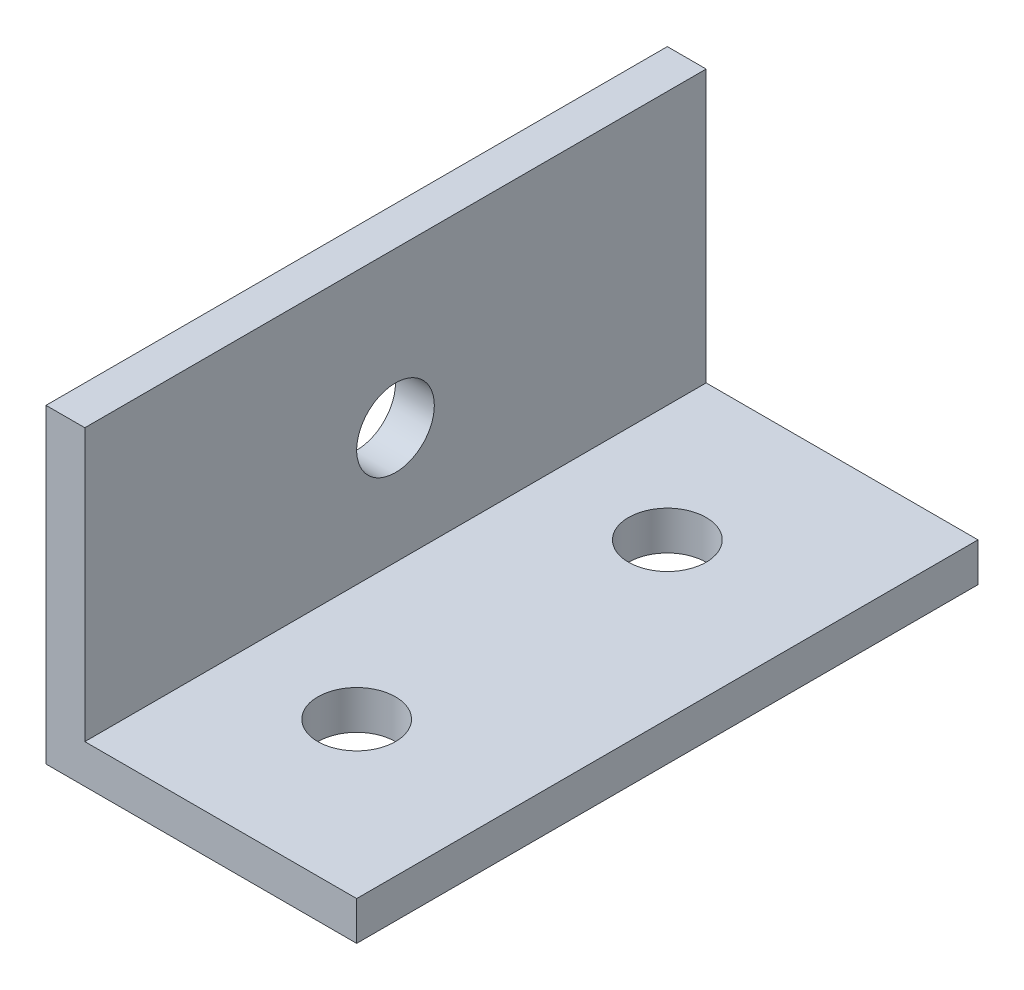
SolidWorks part; units mm, degrees
material "1060 Alloy"
ref_plane "Front Plane" through (0, 0, 0) normal (0, 0, 1) x (1, 0, 0)
ref_plane "Top Plane" through (0, 0, 0) normal (0, 1, 0) x (1, 0, 0)
ref_plane "Right Plane" through (0, 0, 0) normal (1, 0, 0) x (0, 0, -1)
sketch "Sketch1" plane through (0, 0, 0) normal (0, 0, 1) x (1, 0, 0)
  line L0 (0, 0) -> (25.4, 0)
  line L1 (25.4, 0) -> (25.4, 3.175)
  line L2 (25.4, 3.175) -> (3.175, 3.175)
  line L3 (3.175, 3.175) -> (3.175, 25.4)
  line L4 (3.175, 25.4) -> (0, 25.4)
  line L5 (0, 25.4) -> (0, 0)
  dimension "D1" = 25.4
  dimension "D2" = 25.4
  dimension "D3" = 22.225
  dimension "D4" = 22.225
extrude "Boss-Extrude1" add sketch "Sketch1" along normal blind 50.8
sketch "Sketch2" plane through (3.175, 0, 0) normal (1, 0, 0) x (0, 0, -1)
  line L0 (-50.8, 3.175) -> (-50.8, 25.4) construction
  line L1 (-50.8, 3.175) -> (0, 3.175) construction
  circle A0 centre (-25.4, 12.7) radius 3.175
  dimension "D1" = 6.35
  dimension "D2" = 25.4
  dimension "D3" = 9.525
extrude "Cut-Extrude1" cut sketch "Sketch2" against normal through all
sketch "Sketch3" plane through (0, 3.175, 0) normal (0, 1, 0) x (1, 0, 0)
  line L0 (25.4, -50.8) -> (3.175, -50.8) construction
  line L1 (25.4, 0) -> (3.175, 0) construction
  line L2 (3.175, -50.8) -> (3.175, 0) construction
  circle A0 centre (12.7, -38.1) radius 3.175
  circle A1 centre (12.7, -12.7) radius 3.175
  dimension "D3" = 6.35
  dimension "D1" = 12.7
  dimension "D2" = 12.7
  dimension "D4" = 9.525
extrude "Cut-Extrude2" cut sketch "Sketch3" against normal through all
